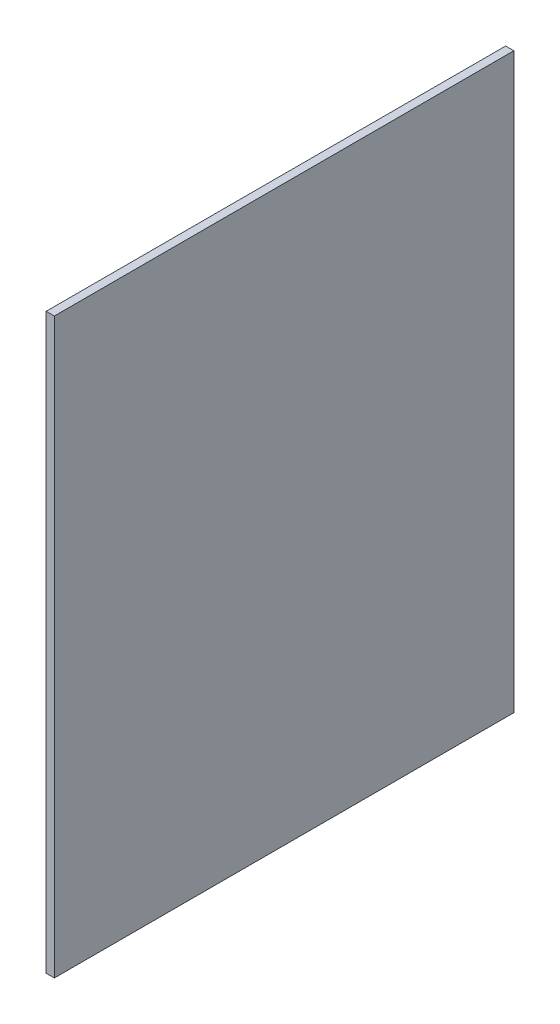
SolidWorks part; units mm, degrees
ref_plane "Alzado" through (0, 0, 0) normal (0, 0, 1) x (1, 0, 0)
ref_plane "Planta" through (0, 0, 0) normal (0, 1, 0) x (1, 0, 0)
ref_plane "Vista lateral" through (0, 0, 0) normal (1, 0, 0) x (0, 0, -1)
sketch "Croquis1" plane through (0, 0, 0) normal (1, 0, 0) x (0, 0, -1)
  line L1 (-104.4719, -60.4649) -> (176.0281, -60.4649)
  line L2 (-104.4719, -60.4649) -> (-104.4719, 289.5351)
  line L3 (-104.4719, 289.5351) -> (176.0281, 289.5351)
  line L4 (176.0281, -60.4649) -> (176.0281, 289.5351)
  dimension "D1" = 280.5
  dimension "D2" = 350
extrude "Saliente-Extruir1" add sketch "Croquis1" along normal blind 5
